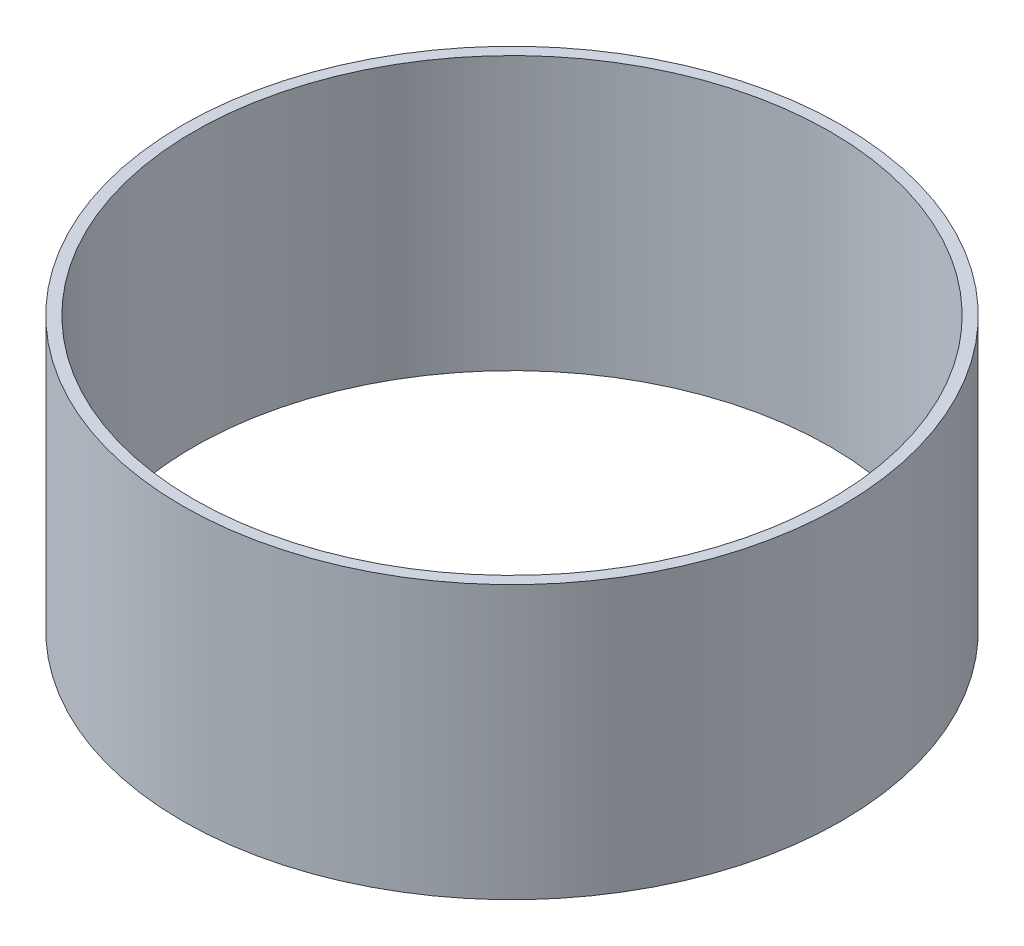
SolidWorks part; units mm, degrees
material "Acrylic (Medium-high impact)"
ref_plane "Front Plane" through (0, 0, 0) normal (0, 0, 1) x (1, 0, 0)
ref_plane "Top Plane" through (0, 0, 0) normal (0, 1, 0) x (1, 0, 0)
ref_plane "Right Plane" through (0, 0, 0) normal (1, 0, 0) x (0, 0, -1)
sketch "Sketch1" plane through (0, 0, 0) normal (0, 1, 0) x (1, 0, 0)
  circle A0 centre (0, 0) radius 92.075
  circle A1 centre (0, 0) radius 88.9
  dimension "D1" = 184.15
  dimension "D2" = 177.8
extrude "Boss-Extrude1" add sketch "Sketch1" along normal mid plane 76.2
ref_plane "Plane1" through (92.075, 0, 0) normal (1, 0, 0) x (0, 0, -1)
sketch "Sketch3" plane through (92.075, 0, 0) normal (1, 0, 0) x (0, 0, -1)
  line L0 (0, 103.0288) -> (0, -103.0288) construction
  line L1 (88.9, 38.1) -> (-88.9, 38.1) construction
  line L2 (-92.075, -38.1) -> (92.075, -38.1) construction
  circle A0 centre (0, -31.75) radius 1.4351
  circle A1 centre (0, 31.75) radius 1.4351
  dimension "D1" = 6.35
  dimension "D2" = 2.8702
  dimension "D3" = 2.8702
  dimension "D4" = 6.35
extrude "Cut-Extrude1" [suppressed] cut sketch "Sketch3" against normal blind 34.798
pattern_circular "CirPattern1" [suppressed] count 3 over 360
